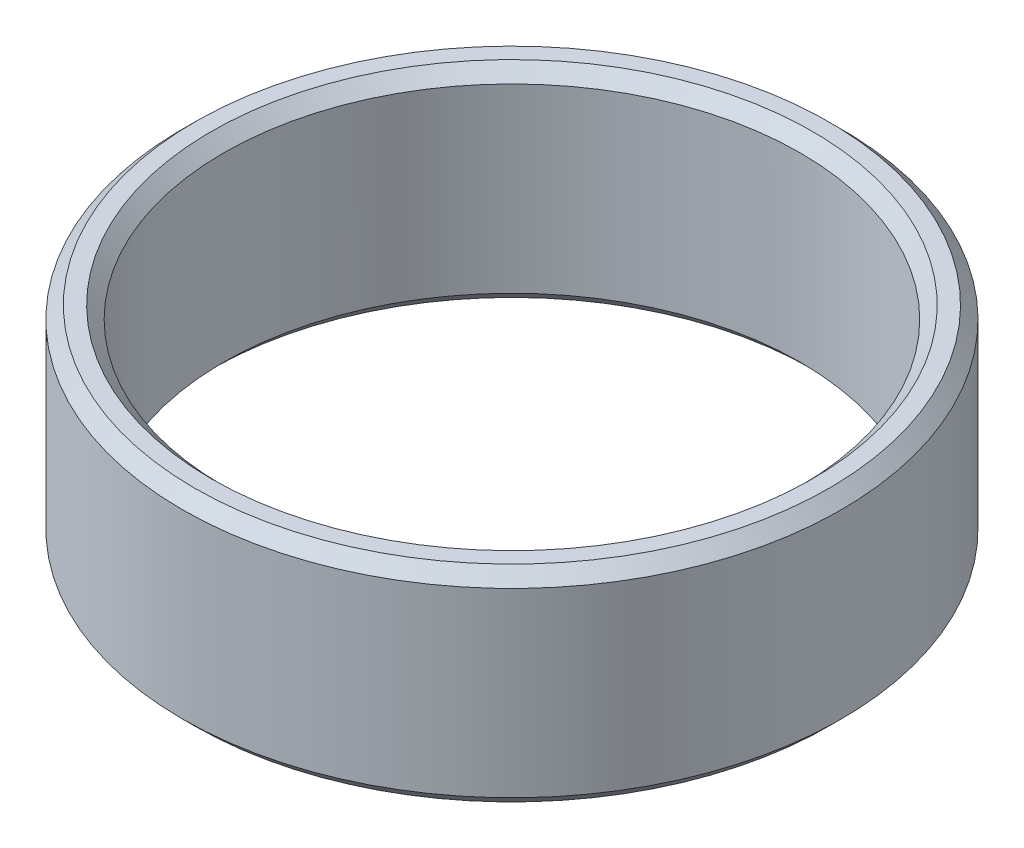
SolidWorks part; units mm, degrees
ref_plane "Front Plane" through (0, 0, 0) normal (0, 0, 1) x (1, 0, 0)
ref_plane "Top Plane" through (0, 0, 0) normal (0, 1, 0) x (1, 0, 0)
ref_plane "Right Plane" through (0, 0, 0) normal (1, 0, 0) x (0, 0, -1)
sketch "Sketch1" plane through (0, 0, 0) normal (0, 1, 0) x (1, 0, 0)
  circle A0 centre (0, 0) radius 7
  circle A1 centre (0, 0) radius 8
  dimension "D1" = 14
  dimension "D2" = 16
extrude "Boss-Extrude1" add sketch "Sketch1" along normal blind 5
chamfer "Chamfer1" distance 0.3 angle 45 4 edges at (0, 0, 8) (0, 5, 8) (0, 0, 7) (0, 5, 7)
